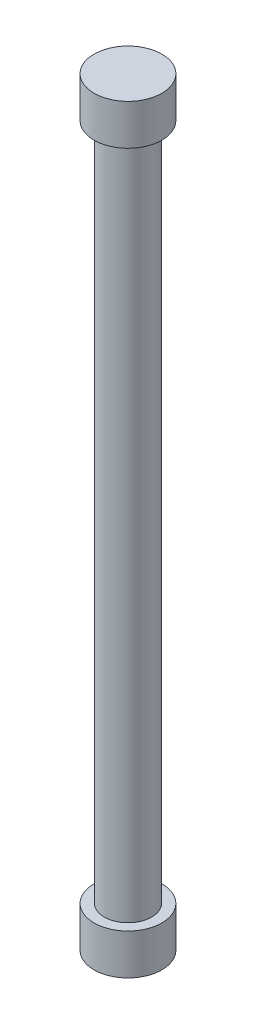
SolidWorks part; units mm, degrees
ref_plane "Front Plane" through (0, 0, 0) normal (0, 0, 1) x (1, 0, 0)
ref_plane "Top Plane" through (0, 0, 0) normal (0, 1, 0) x (1, 0, 0)
ref_plane "Right Plane" through (0, 0, 0) normal (1, 0, 0) x (0, 0, -1)
sketch "Sketch2" plane through (0, 0, 0) normal (0, 1, 0) x (1, 0, 0)
  circle A0 centre (0, 0) radius 2.5
  dimension "D1" = 5
extrude "Boss-Extrude1" add sketch "Sketch2" along normal blind 3
sketch "Sketch3" plane through (0, 3, 0) normal (0, 1, 0) x (1, 0, 0)
  circle A0 centre (0, 0) radius 1.75
  dimension "D1" = 3.5
extrude "Boss-Extrude2" add sketch "Sketch3" along normal blind 50
sketch "Sketch4" plane through (0, 53, 0) normal (0, 1, 0) x (1, 0, 0)
  circle A0 centre (0, 0) radius 2.5
  dimension "D1" = 5
extrude "Boss-Extrude3" add sketch "Sketch4" along normal blind 3
